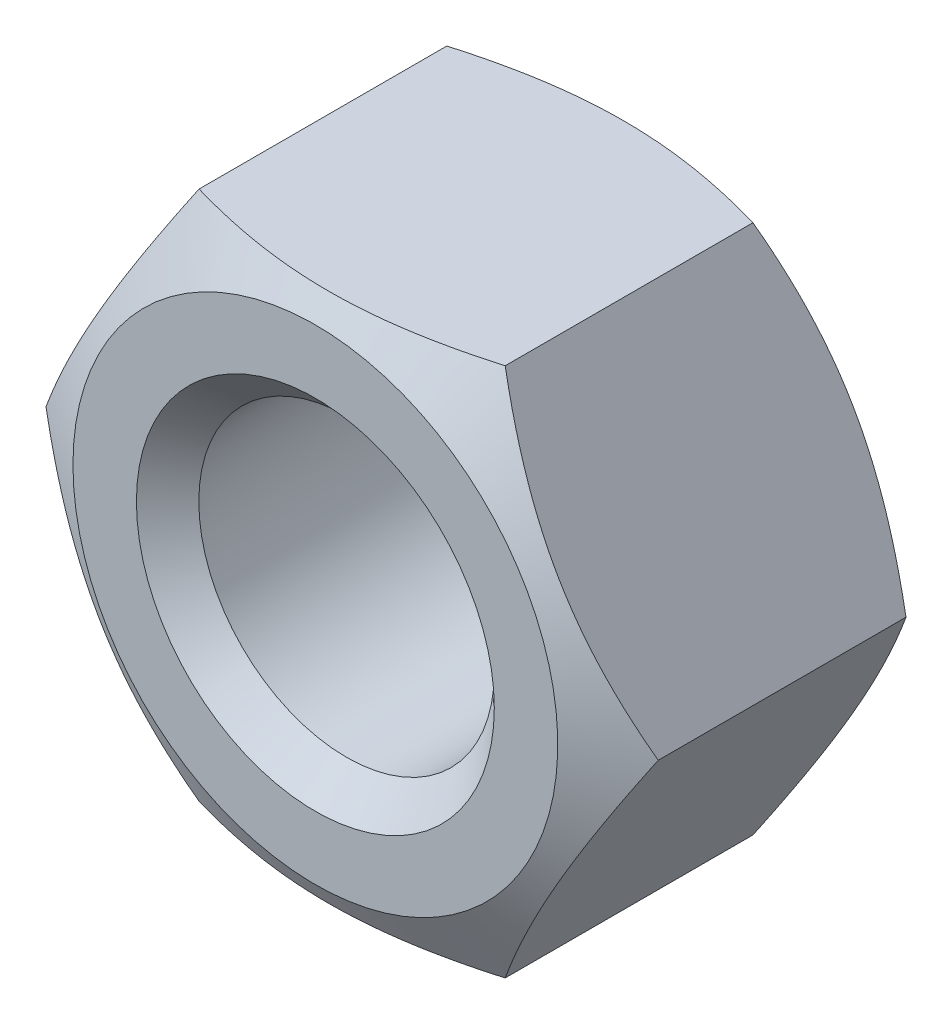
SolidWorks part; units mm, degrees
ref_plane "Front" through (0, 0, 0) normal (0, 0, 1) x (1, 0, 0)
ref_plane "Top" through (0, 0, 0) normal (0, 1, 0) x (1, 0, 0)
ref_plane "Right" through (0, 0, 0) normal (1, 0, 0) x (0, 0, -1)
sketch "Sketch1" plane through (0, 0, 0) normal (0, 0, 1) x (1, 0, 0)
  line L1 (4.6188, -8) -> (9.2376, 0)
  line L2 (9.2376, 0) -> (4.6188, 8)
  line L3 (4.6188, 8) -> (-4.6188, 8)
  line L4 (-4.6188, 8) -> (-9.2376, 0)
  line L5 (-9.2376, 0) -> (-4.6188, -8)
  line L6 (-4.6188, -8) -> (4.6188, -8)
  circle A0 centre (0, 0) radius 8 construction
  circle A1 centre (0, 0) radius 4.4585
extrude "BaseNut" add sketch "Sketch1" against normal blind 9.3
cosmetic thread "ThreadCosmetic1" parameters "D2"=10.8
sketch "Sketch2" plane through (15.0481, 0, -16.7061) normal (0, 1, 0) x (0, 0, -1)
  line L0 (-23.7227, 15.0481) -> (22.0646, 15.0481) construction
  line L2 (-7.4061, 24.2857) -> (-7.4061, 19.6669) construction
  line L4 (-7.4061, 24.2857) -> (-16.7061, 24.2857) construction
  line L8 (-8.1207, 24.2857) -> (-7.4061, 23.0481)
  line L9 (-7.4061, 24.2857) -> (-8.1207, 24.2857)
  line L10 (-7.4061, 23.0481) -> (-7.4061, 24.2857)
  dimension "D1" = 30
revolve "Chamfer1" cut sketch "Sketch2" angle 360 about L0
sketch "Sketch6" plane through (-9.1975, 0, -10.2525) normal (0, 1, 0) x (0, 0, 1)
  line L0 (23.3574, 9.1975) -> (-22.3023, 9.1975) construction
  line L2 (0.9525, 13.656) -> (0.9525, 14.5975)
  line L4 (0.9525, 14.5975) -> (1.4961, 13.656)
  line L6 (1.4961, 13.656) -> (0.9525, 13.656)
  dimension "D2" = 60
revolve "EndChamfer1" cut sketch "Sketch6" angle 360 about L0
sketch "Sketch5" plane through (-14.793, 0, -16.9612) normal (0, 1, 0) x (0, 0, 1)
  line L0 (-22.5748, 14.793) -> (24.743, 14.793) construction
  line L2 (16.9612, 22.108) -> (16.9612, 24.0306)
  line L4 (16.9612, 24.0306) -> (15.8512, 24.0306)
  line L6 (15.8512, 24.0306) -> (16.9612, 22.108)
  dimension "dw1" = 14.63
  dimension "D2" = 30
revolve "Chamfer2" cut sketch "Sketch5" angle 360 about L0
sketch "Sketch3" plane through (-20.9491, 1.8856, 0) normal (0, 0, 1) x (1, 0, 0)
  circle A1 centre (20.9491, -1.8856) radius 4.4585 construction
  circle A2 centre (20.9491, -1.8856) radius 7.315
  circle A3 centre (20.9491, -1.8856) radius 4.4585
  dimension "dw" = 14.63
extrude "Extrude1" [suppressed] add sketch "Sketch3" along normal blind 0.6
chamfer "EndChamfer3" [suppressed] distance 0.31 angle 45
chamfer "EndChamfer2" distance 0.9415 angle 45 1 edges at (4.4585, 0, 0)
sketch "Sketch7" plane through (0, 0, 0) normal (0, 1, 0) x (1, 0, 0)
  line L0 (0, 48.6183) -> (0, -13.0076) construction
  line L1 (3.517, 9.2272) -> (4.4585, 9.2272)
  line L2 (4.4585, 9.2272) -> (5.2739, 8.7564)
  line L3 (5.2739, 8.7564) -> (4.4585, 8.2857)
  line L4 (4.4585, 8.2857) -> (3.517, 8.2857)
  line L5 (3.517, 8.2857) -> (3.517, 9.2272)
  line L6 (4.4585, 8.7564) -> (-4.4585, 8.7564) construction
revolve "Cut-Revolve10" [suppressed] cut sketch "Sketch7" angle 360 about L0
pattern_linear "LPattern10" [suppressed] count 7 spacing 1.1298 along (0, 0, -1)
equation "\"D1@EndChamfer3\" = \"m@BaseNut\" / 30"
equation "\"s1@Sketch2\" = \"s@Sketch1\""
equation "\"D2@Sketch7\" = \"D1@Sketch1\""
equation "\"D1@Sketch7\" = (  \"D2@ThreadCosmetic1\" - \"D1@Sketch1\" )  / 2"
equation "\"D3@LPattern10\" = \"D1@Sketch7\" * 1.2"
equation "\"D1@LPattern10\" = \"m@BaseNut\" / \"D3@LPattern10\" - 1"
equation "\"D1@EndChamfer2\" = (  \"da@Sketch6\" - \"D1@Sketch1\" )  / 2"
